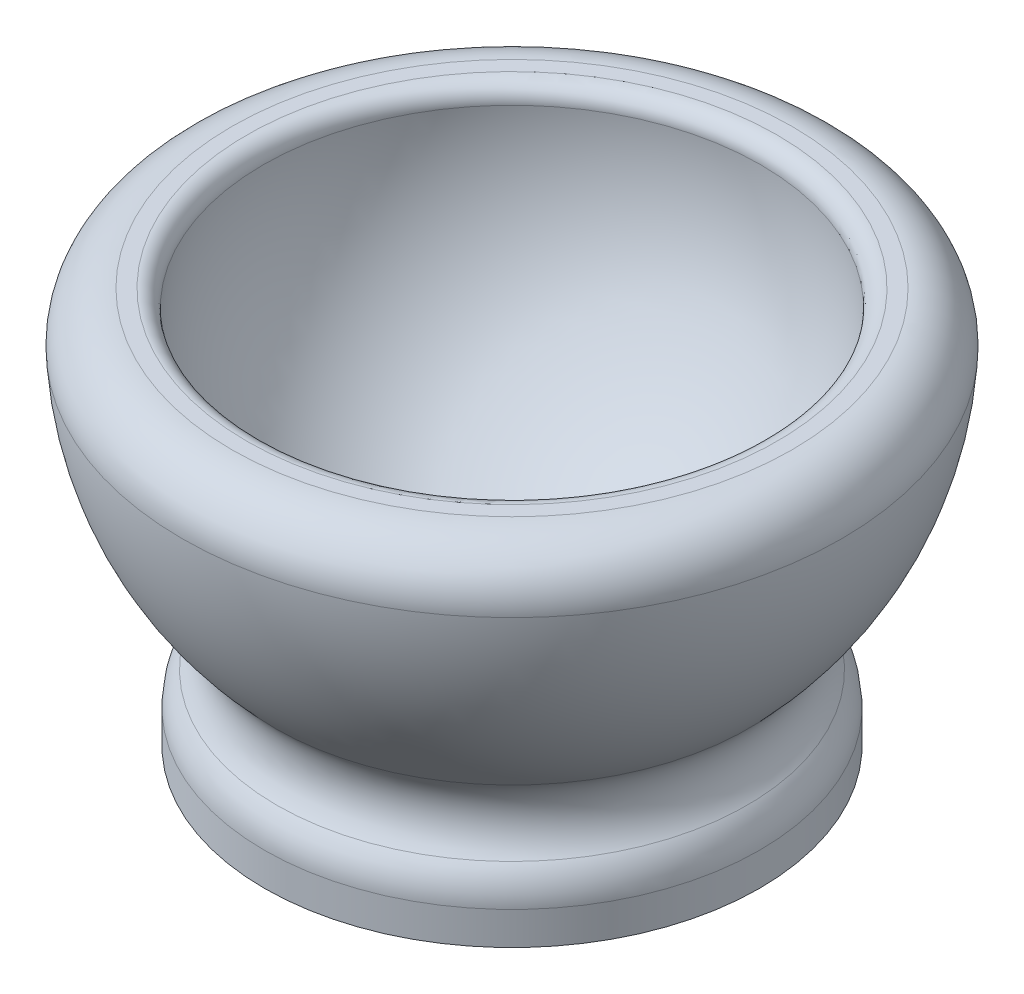
SolidWorks part; units mm, degrees
ref_plane "前视基准面" through (0, 0, 0) normal (0, 0, 1) x (1, 0, 0)
ref_plane "上视基准面" through (0, 0, 0) normal (0, 1, 0) x (1, 0, 0)
ref_plane "右视基准面" through (0, 0, 0) normal (1, 0, 0) x (0, 0, -1)
other "Configuration Table"
sketch "草图1" plane through (0, 0, 0) normal (0, 1, 0) x (1, 0, 0)
  line L0 (-24.0835, 0) -> (25.1351, 0) construction
  line L1 (-15.1, 0) -> (-20, 0)
  line L2 (20, 0) -> (15.1, 0)
  arc A0 (-20, 0) -> (20, 0) centre (0, 0) ccw
  arc A1 (-15.1, 0) -> (15.1, 0) centre (0, 0) ccw
  circle A3 centre (0, 0) radius 20 construction
  circle A4 centre (0, 0) radius 15.1 construction
  point P1 (15, 0)
  point P7 (19.1261, 5.8474)
  dimension "D1" = 40
  dimension "D2" = 4.9
revolve "旋转5" add sketch "草图1" angle 360 about L0
sketch "草图2" plane through (0, 0, 0) normal (1, 0, 0) x (0, 0, -1)
  line L1 (-37.1806, 35) -> (36.2954, 35)
  line L2 (-37.1806, 35) -> (-37.1806, 2)
  line L3 (-37.1806, 2) -> (36.2954, 2)
  line L4 (36.2954, 35) -> (36.2954, 2)
  dimension "D1" = 35
  dimension "D2" = 2
extrude "切除-拉伸1" cut sketch "草图2" against normal through all and the other way through all
fillet "圆角1" radius 1 1 edges at (0, 2, -14.967)
ref_plane "基准面1" through (0, -22, 0) normal (0, 1, 0) x (1, 0, 0)
sketch "草图3" plane through (0, -22, 0) normal (0, 1, 0) x (1, 0, 0)
  circle A0 centre (0, 0) radius 6
  dimension "D1" = 12
extrude "凸台-拉伸1" add sketch "草图3" along normal up to next
sketch "草图4" plane through (0, -22, 0) normal (0, -1, 0) x (-1, 0, 0)
  circle A0 centre (0, 0) radius 15
  dimension "D1" = 30
extrude "凸台-拉伸2" add sketch "草图4" against normal blind 5
fillet "圆角3" radius 3 1 edges at (0, 2, -19.8997)
fillet "圆角4" radius 3 1 edges at (0, -17, -15)
fillet "圆角5" radius 3 1 edges at (0, -17, -10.5357)
